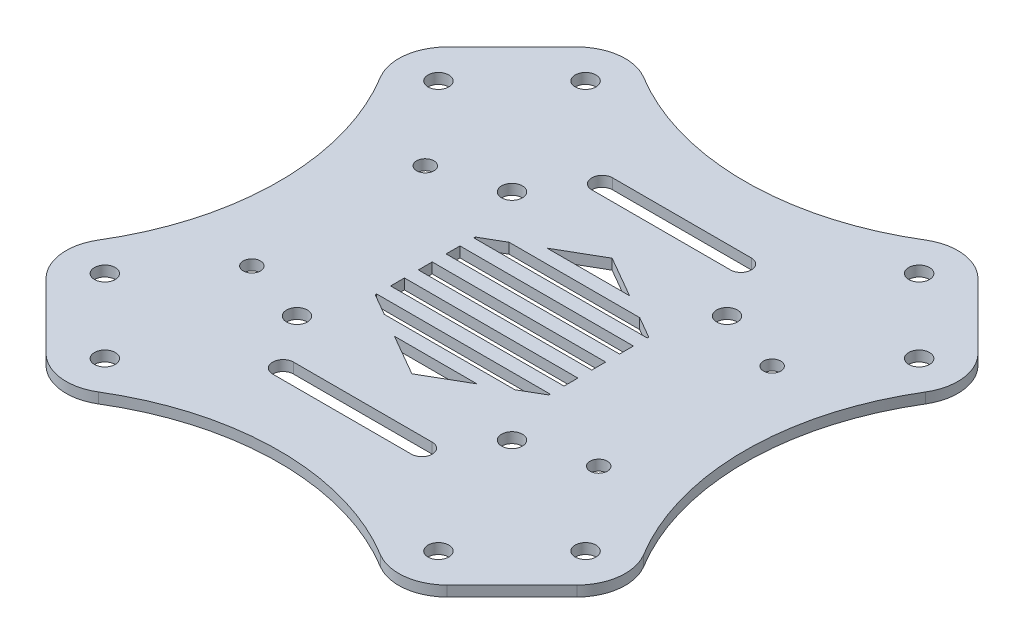
SolidWorks part; units mm, degrees
material "A-Glass Fiber"
ref_plane "Front Plane" through (0, 0, 0) normal (0, 0, 1) x (1, 0, 0)
ref_plane "Top Plane" through (0, 0, 0) normal (0, 1, 0) x (1, 0, 0)
ref_plane "Right Plane" through (0, 0, 0) normal (1, 0, 0) x (0, 0, -1)
sketch "Sketch1" plane through (0, 0, 0) normal (0, 1, 0) x (1, 0, 0)
  line L0 (67.1751, 67.1751) -> (0, 0) construction
  line L1 (0, 0) -> (67.1751, 0) construction
  line L2 (0, 0) -> (0, 67.1751) construction
  line L3 (0, 67.1751) -> (67.1751, 67.1751) construction
  line L4 (67.1751, 0) -> (67.1751, 67.1751) construction
  line L5 (0, 67.1751) -> (67.1751, 0) construction
  line L6 (76.014, 8.8388) -> (8.8388, 76.014) construction
  line L7 (76.014, 8.8388) -> (58.3363, -8.8388)
  line L8 (8.8388, 76.014) -> (-8.8388, 58.3363)
  line L9 (58.3363, -8.8388) -> (-8.8388, 58.3363) construction
  line L10 (76.014, 8.8388) -> (-8.8388, 58.3363) construction
  line L11 (8.8388, 76.014) -> (58.3363, -8.8388) construction
  line L12 (-8.8388, 8.8388) -> (58.3363, 76.014) construction
  line L13 (-8.8388, 8.8388) -> (8.8388, -8.8388)
  line L14 (58.3363, 76.014) -> (76.014, 58.3363)
  line L15 (8.8388, -8.8388) -> (76.014, 58.3363) construction
  line L16 (-8.8388, 8.8388) -> (76.014, 58.3363) construction
  line L17 (58.3363, 76.014) -> (8.8388, -8.8388) construction
  arc A0 (8.8388, 76.014) -> (58.3363, 76.014) centre (33.5876, 106.2428) ccw
  arc A1 (76.014, 58.3363) -> (76.014, 8.8388) centre (106.2428, 33.5876) ccw
  arc A2 (58.3363, -8.8388) -> (8.8388, -8.8388) centre (33.5876, -39.0676) ccw
  arc A3 (-8.8388, 8.8388) -> (-8.8388, 58.3363) centre (-39.0676, 33.5876) ccw
  point P5 (33.5876, 33.5876)
  point P7 (33.5876, 33.5876)
  dimension "D1" = 95
  dimension "D3" = 25
  dimension "D4" = 25
extrude "Boss-Extrude1" add sketch "Sketch1" along normal blind 1.5
sketch "Sketch2" plane through (0, 1.5, 0) normal (0, 1, 0) x (1, 0, 0)
  line L0 (0, 0) -> (67.1751, 67.1751) construction
  line L1 (76.014, 58.3363) -> (58.3363, 76.014) construction
  line L2 (57.6292, 68.2358) -> (68.2358, 57.6292) construction
  circle A0 centre (57.6292, 68.2358) radius 1.5
  circle A1 centre (68.2358, 57.6292) radius 1.5
  circle A2 centre (68.2358, 9.5459) radius 1.5
  circle A3 centre (57.6292, -1.0607) radius 1.5
  circle A4 centre (9.5459, -1.0607) radius 1.5
  circle A5 centre (-1.0607, 9.5459) radius 1.5
  circle A6 centre (-1.0607, 57.6292) radius 1.5
  circle A7 centre (9.5459, 68.2358) radius 1.5
  point P7 (62.9325, 62.9325)
  point P10 (33.5876, 33.5876)
  point P26 (33.5876, 33.5876)
  dimension "D3" = 3
  dimension "D4" = 3
  dimension "D1" = 15
  dimension "D2" = 6
  dimension "D5" = 4
extrude "Cut-Extrude1" cut sketch "Sketch2" against normal through all
fillet "Fillet1" radius 7 8 edges at (-8.8388, 0.75, -8.8388) (8.8388, 0.75, 8.8388) (58.3363, 0.75, 8.8388) (76.014, 0.75, -8.8388) (76.014, 0.75, -58.3363) (58.3363, 0.75, -76.014) (-8.8388, 0.75, -58.3363) (8.8388, 0.75, -76.014)
sketch "Sketch3" plane through (0, 1.5, 0) normal (0, 1, 0) x (1, 0, 0)
  line L0 (33.5876, 67.1751) -> (33.5876, 0) construction
  line L1 (18.0876, 49.0876) -> (18.0876, 18.0876) construction
  line L2 (15.5876, 15.5876) -> (51.5876, 15.5876) construction
  line L3 (15.5876, 15.5876) -> (15.5876, 51.5876) construction
  line L4 (15.5876, 51.5876) -> (51.5876, 51.5876) construction
  line L5 (51.5876, 15.5876) -> (51.5876, 51.5876) construction
  line L6 (15.5876, 15.5876) -> (51.5876, 51.5876) construction
  line L7 (15.5876, 51.5876) -> (51.5876, 15.5876) construction
  circle A2 centre (18.0876, 49.0876) radius 1.5
  circle A3 centre (18.0876, 18.0876) radius 1.5
  circle A4 centre (49.0876, 18.0876) radius 1.5
  circle A5 centre (49.0876, 49.0876) radius 1.5
  arc A6 (13.2647, 72.8772) -> (53.9105, 72.8772) centre (33.5876, 106.2428) ccw construction
  arc A7 (53.9105, -5.7021) -> (13.2647, -5.7021) centre (33.5876, -39.0676) ccw construction
  point P8 (33.5876, 33.5876)
  point P9 (33.5876, 33.5876)
  point P22 (33.5876, 33.5876)
  dimension "D2" = 3
  dimension "D3" = 3
  dimension "D1" = 36
  dimension "D4" = 31
extrude "Cut-Extrude2" cut sketch "Sketch3" against normal through all
sketch "Sketch5" plane through (0, 1.5, 0) normal (0, 1, 0) x (1, 0, 0)
  line L0 (33.5876, 67.1751) -> (33.5876, 0) construction
  arc A0 (13.2647, 72.8772) -> (53.9105, 72.8772) centre (33.5876, 106.2428) ccw construction
  arc A1 (53.9105, -5.7021) -> (13.2647, -5.7021) centre (33.5876, -39.0676) ccw construction
  circle A2 centre (33.5876, 59.5876) radius 1.5 construction
  circle A3 centre (59.5876, 33.5876) radius 1.5 construction
  circle A4 centre (33.5876, 7.5876) radius 1.5 construction
  circle A5 centre (7.5876, 33.5876) radius 1.5 construction
  point P8 (33.5876, 33.5876)
  point P20 (33.5876, 33.5876)
  dimension "D1" = 3
  dimension "D2" = 26
  dimension "D3" = 4
sketch "Sketch6" plane through (0, 1.5, 0) normal (0, 1, 0) x (1, 0, 0)
  line L0 (33.5876, 67.1751) -> (33.5876, 0) construction
  line L1 (0, 33.5876) -> (67.1751, 33.5876) construction
  line L2 (23.5876, 56.5876) -> (43.5876, 56.5876) construction
  line L3 (23.5876, 58.0876) -> (43.5876, 58.0876)
  line L4 (23.5876, 55.0876) -> (43.5876, 55.0876)
  line L5 (23.5876, 10.5876) -> (43.5876, 10.5876) construction
  line L6 (23.5876, 9.0876) -> (43.5876, 9.0876)
  line L7 (23.5876, 12.0876) -> (43.5876, 12.0876)
  line L8 (58.5876, 46.0876) -> (58.5876, 21.0876) construction
  line L9 (8.5876, 46.0876) -> (8.5876, 21.0876) construction
  line L11 (33.5876, 48.0213) -> (21.0876, 40.8045)
  line L12 (21.0876, 40.8045) -> (21.0876, 26.3707)
  line L13 (21.0876, 26.3707) -> (33.5876, 19.1538)
  line L14 (33.5876, 19.1538) -> (46.0876, 26.3707)
  line L15 (46.0876, 26.3707) -> (46.0876, 40.8045)
  line L16 (46.0876, 40.8045) -> (33.5876, 48.0213)
  arc A0 (13.2647, 72.8772) -> (53.9105, 72.8772) centre (33.5876, 106.2428) ccw construction
  arc A1 (53.9105, -5.7021) -> (13.2647, -5.7021) centre (33.5876, -39.0676) ccw construction
  arc A2 (-5.7021, 13.2647) -> (-5.7021, 53.9105) centre (-39.0676, 33.5876) ccw construction
  arc A3 (72.8772, 53.9105) -> (72.8772, 13.2647) centre (106.2428, 33.5876) ccw construction
  arc A4 (23.5876, 58.0876) -> (23.5876, 55.0876) centre (23.5876, 56.5876) ccw
  arc A5 (43.5876, 55.0876) -> (43.5876, 58.0876) centre (43.5876, 56.5876) ccw
  arc A6 (23.5876, 9.0876) -> (23.5876, 12.0876) centre (23.5876, 10.5876) cw
  arc A7 (43.5876, 12.0876) -> (43.5876, 9.0876) centre (43.5876, 10.5876) cw
  circle A8 centre (58.5876, 46.0876) radius 1.25
  circle A9 centre (58.5876, 21.0876) radius 1.25
  circle A10 centre (8.5876, 21.0876) radius 1.25
  circle A11 centre (8.5876, 46.0876) radius 1.25
  circle A12 centre (33.5876, 33.5876) radius 12.5 construction
  point P8 (33.5876, 33.5876)
  point P19 (33.5876, 56.5876)
  point P26 (33.5876, 10.5876)
  point P33 (58.5876, 33.5876)
  point P36 (8.5876, 33.5876)
  dimension "D4" = 2.5
  dimension "D5" = 2.5
  dimension "D8" = 25
  dimension "D1" = 3
  dimension "D2" = 20
  dimension "D3" = 23
  dimension "D6" = 25
  dimension "D7" = 25
extrude "Cut-Extrude3" cut sketch "Sketch6" against normal through all
sketch "Sketch8" plane through (0, 1.5, 0) normal (0, 1, 0) x (1, 0, 0)
  line L0 (33.5876, 48.0213) -> (33.5876, 19.1538) construction
  line L1 (21.0876, 40.8045) -> (21.0876, 26.3707) construction
  line L2 (46.0876, 34.5876) -> (21.0876, 34.5876)
  line L3 (46.0876, 34.5876) -> (46.0876, 32.5876)
  line L4 (46.0876, 32.5876) -> (21.0876, 32.5876)
  line L5 (21.0876, 34.5876) -> (21.0876, 32.5876)
  line L6 (46.0876, 34.5876) -> (21.0876, 32.5876) construction
  line L7 (46.0876, 32.5876) -> (21.0876, 34.5876) construction
  line L8 (46.0876, 30.5876) -> (21.0876, 30.5876)
  line L9 (46.0876, 28.5876) -> (21.0876, 28.5876)
  line L10 (46.0876, 26.5876) -> (21.0876, 26.5876)
  line L11 (46.0876, 24.5876) -> (21.0876, 24.5876)
  line L12 (46.0876, 22.5876) -> (21.0876, 22.5876)
  line L13 (46.0876, 20.5876) -> (21.0876, 20.5876)
  line L14 (46.0876, 34.5876) -> (21.0876, 34.5876)
  line L15 (46.0876, 32.5876) -> (21.0876, 32.5876)
  line L16 (46.0876, 30.5876) -> (21.0876, 30.5876)
  line L17 (46.0876, 28.5876) -> (21.0876, 28.5876)
  line L18 (46.0876, 26.5876) -> (21.0876, 26.5876)
  line L19 (46.0876, 24.5876) -> (21.0876, 24.5876)
  line L20 (46.0876, 38.5876) -> (21.0876, 38.5876)
  line L21 (46.0876, 36.5876) -> (21.0876, 36.5876)
  line L22 (46.0876, 34.5876) -> (21.0876, 34.5876)
  line L23 (46.0876, 32.5876) -> (21.0876, 32.5876)
  line L24 (46.0876, 30.5876) -> (21.0876, 30.5876)
  line L25 (46.0876, 28.5876) -> (21.0876, 28.5876)
  line L26 (46.0876, 42.5876) -> (21.0876, 42.5876)
  line L27 (46.0876, 40.5876) -> (21.0876, 40.5876)
  line L28 (46.0876, 38.5876) -> (21.0876, 38.5876)
  line L29 (46.0876, 36.5876) -> (21.0876, 36.5876)
  line L30 (46.0876, 34.5876) -> (21.0876, 34.5876)
  line L31 (46.0876, 32.5876) -> (21.0876, 32.5876)
  line L32 (46.0876, 38.5876) -> (21.0876, 38.5876)
  line L33 (46.0876, 36.5876) -> (21.0876, 36.5876)
  line L34 (46.0876, 42.5876) -> (21.0876, 42.5876)
  line L35 (46.0876, 40.5876) -> (21.0876, 40.5876)
  line L36 (46.0876, 46.5876) -> (21.0876, 46.5876)
  line L37 (46.0876, 44.5876) -> (21.0876, 44.5876)
  line L38 (21.0876, 46.5876) -> (21.0876, 20.5876)
  line L39 (46.0876, 20.5876) -> (46.0876, 46.5876)
  point P4 (33.5876, 33.5876)
  point P11 (-16.0887, 64.7486)
  line M1 (33.5876, 48.0213) -> (46.0876, 40.8045)
  line M2 (46.0876, 40.8045) -> (46.0876, 26.3707)
  line M3 (46.0876, 26.3707) -> (33.5876, 19.1538)
  line M4 (33.5876, 19.1538) -> (21.0876, 26.3707)
  line M5 (21.0876, 26.3707) -> (21.0876, 40.8045)
  line M6 (21.0876, 40.8045) -> (33.5876, 48.0213)
extrude "Boss-Extrude2" add sketch "Sketch8" against normal through all contours L21 L2 M2 M5 | L8 L4 M2 M5 | L27 L20 M2 M5 | L37 L26 M1 M6 | L10 L9 M2 M5 | L12 L11 M3 M4
